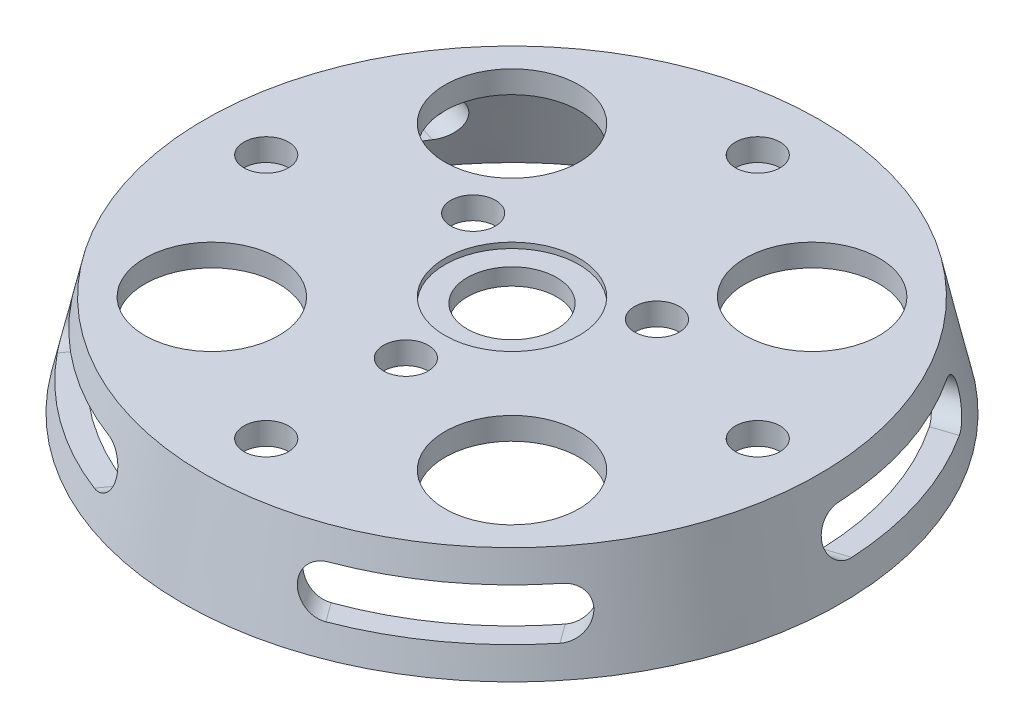
SolidWorks part; units mm, degrees
ref_plane "Front Plane" through (0, 0, 0) normal (0, 0, 1) x (1, 0, 0)
ref_plane "Top Plane" through (0, 0, 0) normal (0, 1, 0) x (1, 0, 0)
ref_plane "Right Plane" through (0, 0, 0) normal (1, 0, 0) x (0, 0, -1)
sketch "Sketch1" plane through (0, 0, 0) normal (0, 1, 0) x (1, 0, 0)
  circle A0 centre (0, 0) radius 29.5
  dimension "D1" = 59
ref_plane "Plane1" through (0, 9, 0) normal (0, 1, 0) x (1, 0, 0)
sketch "Sketch2" plane through (0, 9, 0) normal (0, 1, 0) x (1, 0, 0)
  circle A0 centre (0, 0) radius 27.5
  dimension "D1" = 55
loft "Loft1" add profiles "Sketch1", "Sketch2"
shell "Shell1" thickness 2
sketch "Sketch3" plane through (0, 0, 0) normal (0, 0, 1) x (1, 0, 0)
  line L0 (-7.5, 4.5) -> (7.5, 4.5) construction
  line L1 (-7.5, 6.5) -> (7.5, 6.5)
  line L2 (-7.5, 2.5) -> (7.5, 2.5)
  arc A0 (-7.5, 6.5) -> (-7.5, 2.5) centre (-7.5, 4.5) ccw
  arc A1 (7.5, 2.5) -> (7.5, 6.5) centre (7.5, 4.5) ccw
  point P2 (0, 4.5)
  dimension "D4" = 2
  dimension "D1" = 15
  dimension "D2" = 0
  dimension "D3" = 4.5
extrude "Cut-Extrude1" cut sketch "Sketch3" against normal blind 30
pattern_circular "CirPattern1" count 5 over 360 about axis through (0, 9, 0) along (0, -1, 0) of "Cut-Extrude1"
sketch "Sketch4" plane through (0, 9, 0) normal (0, 1, 0) x (1, 0, 0)
  line L0 (0, 0) -> (0, 10) construction
  line L1 (0, 0) -> (13.435, 13.435) construction
  line L2 (13.435, -13.435) -> (0, 0) construction
  circle A0 centre (0, 0) radius 22 construction
  circle A1 centre (0, -22) radius 2
  circle A2 centre (-22, 0) radius 2
  circle A3 centre (0, 22) radius 2
  circle A4 centre (22, 0) radius 2
  circle A5 centre (0, 0) radius 19 construction
  circle A6 centre (13.435, 13.435) radius 6
  circle A7 centre (13.435, -13.435) radius 6
  circle A8 centre (-13.435, -13.435) radius 6
  circle A9 centre (-13.435, 13.435) radius 6
  circle A10 centre (0, 0) radius 4
  circle A11 centre (0, 0) radius 9.5 construction
  circle A12 centre (0, -9.5) radius 2
  circle A13 centre (-8.2272, 4.75) radius 2
  circle A14 centre (8.2272, 4.75) radius 2
  point P14 (0, 0)
  point P25 (0, 0)
  point P33 (0, 0)
  dimension "D1" = 44
  dimension "D2" = 4
  dimension "D4" = 38
  dimension "D5" = 45
  dimension "D8" = 12
  dimension "D10" = 19
  dimension "D11" = 135
  dimension "D12" = 8
  dimension "D13" = 19
  dimension "D14" = 4
  dimension "D6" = 10
  dimension "D7" = 90
  dimension "D3" = 4
  dimension "D9" = 4
  dimension "D15" = 3
extrude "Cut-Extrude2" cut sketch "Sketch4" against normal blind 2
sketch "Sketch5" plane through (0, 9, 0) normal (0, 1, 0) x (1, 0, 0)
  circle A0 centre (0, 0) radius 6
  dimension "D1" = 12
extrude "Cut-Extrude3" cut sketch "Sketch5" against normal blind 0.5
